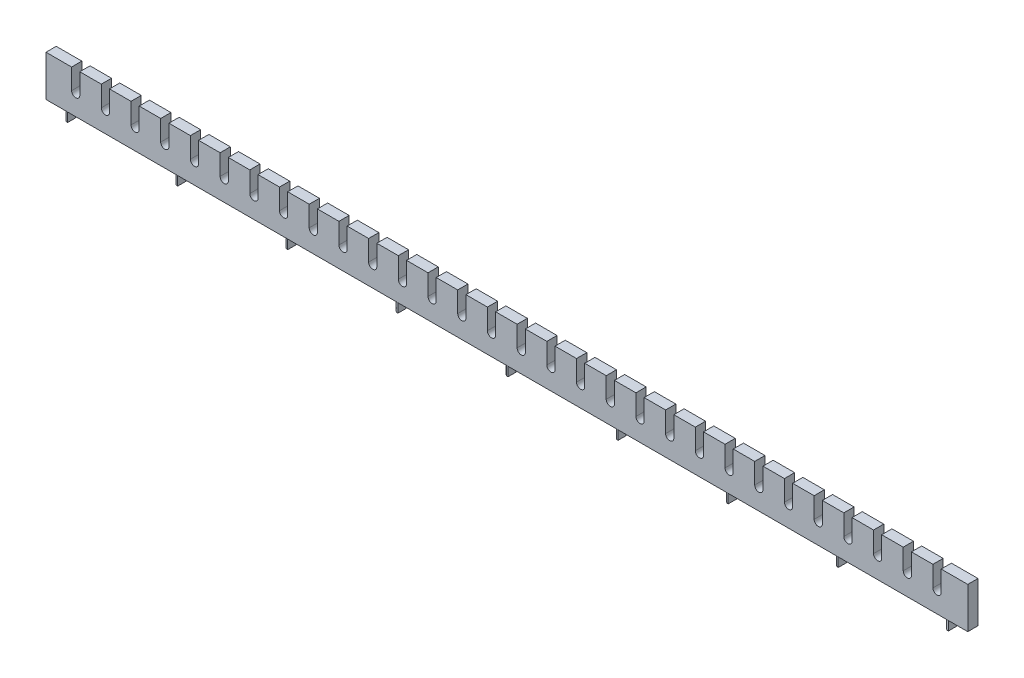
SolidWorks part; units mm, degrees
material "PPE"
ref_plane "Front Plane" through (0, 0, 0) normal (0, 0, 1) x (1, 0, 0)
ref_plane "Top Plane" through (0, 0, 0) normal (0, 1, 0) x (1, 0, 0)
ref_plane "Right Plane" through (0, 0, 0) normal (1, 0, 0) x (0, 0, -1)
sketch "Sketch1" plane through (0, 0, 0) normal (0, 1, 0) x (1, 0, 0)
  line L1 (-285.75, -3.175) -> (285.75, -3.175)
  line L2 (-285.75, -3.175) -> (-285.75, 3.175)
  line L3 (-285.75, 3.175) -> (285.75, 3.175)
  line L4 (285.75, -3.175) -> (285.75, 3.175)
  line L5 (-285.75, -3.175) -> (285.75, 3.175) construction
  line L6 (-285.75, 3.175) -> (285.75, -3.175) construction
  point P0 (0, 0)
  dimension "D1" = 6.35
  dimension "D2" = 571.5
extrude "Boss-Extrude1" add sketch "Sketch1" along normal blind 25.4 contours L2 L3 L4 L1
sketch "Sketch2" plane through (0, 0, 0) normal (0, -1, 0) x (1, 0, 0)
  line L0 (-273.05, 2.54) -> (-273.05, -2.54)
  line L1 (-204.7875, 2.54) -> (-204.7875, -2.54)
  line L2 (-136.525, 2.54) -> (-136.525, -2.54)
  line L3 (-68.2625, 2.54) -> (-68.2625, -2.54)
  line L4 (0, 2.54) -> (0, -2.54)
  line L5 (68.2625, 2.54) -> (68.2625, -2.54)
  line L6 (136.525, 2.54) -> (136.525, -2.54)
  line L7 (204.7875, 2.54) -> (204.7875, -2.54)
  line L8 (273.05, 2.54) -> (273.05, -2.54)
  line L9 (-285.75, 3.175) -> (-285.75, -3.175) construction
  arc A4 (-273.05, 2.54) -> (-273.05, -2.54) centre (-273.05, 0) ccw
  arc A17 (-204.7875, 2.54) -> (-204.7875, -2.54) centre (-204.7875, 0) ccw
  arc A18 (-136.525, 2.54) -> (-136.525, -2.54) centre (-136.525, 0) ccw
  arc A19 (-68.2625, 2.54) -> (-68.2625, -2.54) centre (-68.2625, 0) ccw
  arc A20 (0, 2.54) -> (0, -2.54) centre (0, 0) ccw
  arc A21 (68.2625, 2.54) -> (68.2625, -2.54) centre (68.2625, 0) ccw
  arc A22 (136.525, 2.54) -> (136.525, -2.54) centre (136.525, 0) ccw
  arc A23 (204.7875, 2.54) -> (204.7875, -2.54) centre (204.7875, 0) ccw
  arc A24 (273.05, 2.54) -> (273.05, -2.54) centre (273.05, 0) ccw
  dimension "D1" = 9
  dimension "D4" = 5.08
  dimension "D2" = 12.7
extrude "Boss-Extrude2" add sketch "Sketch2" along normal blind 6.35
sketch "Sketch3" plane through (0, 0, 3.175) normal (0, 0, 1) x (1, 0, 0)
  line L0 (-267.335, 38.1) -> (-267.335, 12.7) construction
  line L1 (-285.75, 25.4) -> (285.75, 25.4) construction
  line L2 (-264.795, 38.1) -> (-264.795, 12.7)
  line L3 (-269.875, 38.1) -> (-269.875, 12.7)
  line L4 (-248.92, 38.1) -> (-248.92, 12.7) construction
  line L7 (-246.38, 38.1) -> (-246.38, 12.7)
  line L10 (-251.46, 38.1) -> (-251.46, 12.7)
  line L19 (-230.505, 38.1) -> (-230.505, 12.7) construction
  line L32 (-227.965, 38.1) -> (-227.965, 12.7)
  line L35 (-233.045, 38.1) -> (-233.045, 12.7)
  line L38 (-212.09, 38.1) -> (-212.09, 12.7) construction
  line L41 (-209.55, 38.1) -> (-209.55, 12.7)
  line L44 (-214.63, 38.1) -> (-214.63, 12.7)
  line L47 (-193.675, 38.1) -> (-193.675, 12.7) construction
  line L50 (-191.135, 38.1) -> (-191.135, 12.7)
  line L53 (-196.215, 38.1) -> (-196.215, 12.7)
  line L56 (-175.26, 38.1) -> (-175.26, 12.7) construction
  line L59 (-172.72, 38.1) -> (-172.72, 12.7)
  line L62 (-177.8, 38.1) -> (-177.8, 12.7)
  line L65 (-156.845, 38.1) -> (-156.845, 12.7) construction
  line L68 (-154.305, 38.1) -> (-154.305, 12.7)
  line L71 (-159.385, 38.1) -> (-159.385, 12.7)
  line L74 (-138.43, 38.1) -> (-138.43, 12.7) construction
  line L77 (-135.89, 38.1) -> (-135.89, 12.7)
  line L80 (-140.97, 38.1) -> (-140.97, 12.7)
  line L83 (-120.015, 38.1) -> (-120.015, 12.7) construction
  line L86 (-117.475, 38.1) -> (-117.475, 12.7)
  line L89 (-122.555, 38.1) -> (-122.555, 12.7)
  line L92 (-101.6, 38.1) -> (-101.6, 12.7) construction
  line L95 (-99.06, 38.1) -> (-99.06, 12.7)
  line L98 (-104.14, 38.1) -> (-104.14, 12.7)
  line L101 (-83.185, 38.1) -> (-83.185, 12.7) construction
  line L104 (-80.645, 38.1) -> (-80.645, 12.7)
  line L105 (-85.725, 38.1) -> (-85.725, 12.7)
  line L106 (-64.77, 38.1) -> (-64.77, 12.7) construction
  line L107 (-62.23, 38.1) -> (-62.23, 12.7)
  line L108 (-67.31, 38.1) -> (-67.31, 12.7)
  line L109 (-46.355, 38.1) -> (-46.355, 12.7) construction
  line L110 (-43.815, 38.1) -> (-43.815, 12.7)
  line L111 (-48.895, 38.1) -> (-48.895, 12.7)
  line L112 (-27.94, 38.1) -> (-27.94, 12.7) construction
  line L113 (-25.4, 38.1) -> (-25.4, 12.7)
  line L114 (-30.48, 38.1) -> (-30.48, 12.7)
  line L115 (-9.525, 38.1) -> (-9.525, 12.7) construction
  line L116 (-285.75, 25.4) -> (-285.75, 0) construction
  line L134 (-6.985, 38.1) -> (-6.985, 12.7)
  line L135 (-12.065, 38.1) -> (-12.065, 12.7)
  line L136 (8.89, 38.1) -> (8.89, 12.7) construction
  line L137 (11.43, 38.1) -> (11.43, 12.7)
  line L138 (6.35, 38.1) -> (6.35, 12.7)
  line L139 (27.305, 38.1) -> (27.305, 12.7) construction
  line L140 (29.845, 38.1) -> (29.845, 12.7)
  line L141 (24.765, 38.1) -> (24.765, 12.7)
  line L142 (45.72, 38.1) -> (45.72, 12.7) construction
  line L143 (48.26, 38.1) -> (48.26, 12.7)
  line L144 (43.18, 38.1) -> (43.18, 12.7)
  line L145 (64.135, 38.1) -> (64.135, 12.7) construction
  line L146 (66.675, 38.1) -> (66.675, 12.7)
  line L147 (61.595, 38.1) -> (61.595, 12.7)
  line L148 (82.55, 38.1) -> (82.55, 12.7) construction
  line L149 (85.09, 38.1) -> (85.09, 12.7)
  line L150 (80.01, 38.1) -> (80.01, 12.7)
  line L151 (100.965, 38.1) -> (100.965, 12.7) construction
  line L152 (103.505, 38.1) -> (103.505, 12.7)
  line L153 (98.425, 38.1) -> (98.425, 12.7)
  line L154 (119.38, 38.1) -> (119.38, 12.7) construction
  line L155 (121.92, 38.1) -> (121.92, 12.7)
  line L156 (116.84, 38.1) -> (116.84, 12.7)
  line L157 (137.795, 38.1) -> (137.795, 12.7) construction
  line L158 (140.335, 38.1) -> (140.335, 12.7)
  line L159 (135.255, 38.1) -> (135.255, 12.7)
  line L160 (156.21, 38.1) -> (156.21, 12.7) construction
  line L161 (158.75, 38.1) -> (158.75, 12.7)
  line L162 (153.67, 38.1) -> (153.67, 12.7)
  line L163 (174.625, 38.1) -> (174.625, 12.7) construction
  line L164 (177.165, 38.1) -> (177.165, 12.7)
  line L165 (172.085, 38.1) -> (172.085, 12.7)
  line L166 (193.04, 38.1) -> (193.04, 12.7) construction
  line L167 (195.58, 38.1) -> (195.58, 12.7)
  line L168 (190.5, 38.1) -> (190.5, 12.7)
  line L169 (211.455, 38.1) -> (211.455, 12.7) construction
  line L170 (213.995, 38.1) -> (213.995, 12.7)
  line L171 (208.915, 38.1) -> (208.915, 12.7)
  line L172 (229.87, 38.1) -> (229.87, 12.7) construction
  line L173 (232.41, 38.1) -> (232.41, 12.7)
  line L174 (227.33, 38.1) -> (227.33, 12.7)
  line L175 (248.285, 38.1) -> (248.285, 12.7) construction
  line L176 (250.825, 38.1) -> (250.825, 12.7)
  line L177 (245.745, 38.1) -> (245.745, 12.7)
  line L178 (266.7, 38.1) -> (266.7, 12.7) construction
  line L179 (269.24, 38.1) -> (269.24, 12.7)
  line L180 (264.16, 38.1) -> (264.16, 12.7)
  arc A0 (-264.795, 38.1) -> (-269.875, 38.1) centre (-267.335, 38.1) ccw
  arc A1 (-269.875, 12.7) -> (-264.795, 12.7) centre (-267.335, 12.7) ccw
  arc A60 (-246.38, 38.1) -> (-251.46, 38.1) centre (-248.92, 38.1) ccw
  arc A61 (-251.46, 12.7) -> (-246.38, 12.7) centre (-248.92, 12.7) ccw
  arc A62 (-227.965, 38.1) -> (-233.045, 38.1) centre (-230.505, 38.1) ccw
  arc A63 (-233.045, 12.7) -> (-227.965, 12.7) centre (-230.505, 12.7) ccw
  arc A64 (-209.55, 38.1) -> (-214.63, 38.1) centre (-212.09, 38.1) ccw
  arc A65 (-214.63, 12.7) -> (-209.55, 12.7) centre (-212.09, 12.7) ccw
  arc A66 (-191.135, 38.1) -> (-196.215, 38.1) centre (-193.675, 38.1) ccw
  arc A67 (-196.215, 12.7) -> (-191.135, 12.7) centre (-193.675, 12.7) ccw
  arc A68 (-172.72, 38.1) -> (-177.8, 38.1) centre (-175.26, 38.1) ccw
  arc A69 (-177.8, 12.7) -> (-172.72, 12.7) centre (-175.26, 12.7) ccw
  arc A70 (-154.305, 38.1) -> (-159.385, 38.1) centre (-156.845, 38.1) ccw
  arc A71 (-159.385, 12.7) -> (-154.305, 12.7) centre (-156.845, 12.7) ccw
  arc A72 (-135.89, 38.1) -> (-140.97, 38.1) centre (-138.43, 38.1) ccw
  arc A73 (-140.97, 12.7) -> (-135.89, 12.7) centre (-138.43, 12.7) ccw
  arc A74 (-117.475, 38.1) -> (-122.555, 38.1) centre (-120.015, 38.1) ccw
  arc A75 (-122.555, 12.7) -> (-117.475, 12.7) centre (-120.015, 12.7) ccw
  arc A76 (-99.06, 38.1) -> (-104.14, 38.1) centre (-101.6, 38.1) ccw
  arc A77 (-104.14, 12.7) -> (-99.06, 12.7) centre (-101.6, 12.7) ccw
  arc A78 (-80.645, 38.1) -> (-85.725, 38.1) centre (-83.185, 38.1) ccw
  arc A79 (-85.725, 12.7) -> (-80.645, 12.7) centre (-83.185, 12.7) ccw
  arc A80 (-62.23, 38.1) -> (-67.31, 38.1) centre (-64.77, 38.1) ccw
  arc A81 (-67.31, 12.7) -> (-62.23, 12.7) centre (-64.77, 12.7) ccw
  arc A82 (-43.815, 38.1) -> (-48.895, 38.1) centre (-46.355, 38.1) ccw
  arc A83 (-48.895, 12.7) -> (-43.815, 12.7) centre (-46.355, 12.7) ccw
  arc A84 (-25.4, 38.1) -> (-30.48, 38.1) centre (-27.94, 38.1) ccw
  arc A85 (-30.48, 12.7) -> (-25.4, 12.7) centre (-27.94, 12.7) ccw
  arc A86 (-6.985, 38.1) -> (-12.065, 38.1) centre (-9.525, 38.1) ccw
  arc A87 (-12.065, 12.7) -> (-6.985, 12.7) centre (-9.525, 12.7) ccw
  arc A88 (11.43, 38.1) -> (6.35, 38.1) centre (8.89, 38.1) ccw
  arc A89 (6.35, 12.7) -> (11.43, 12.7) centre (8.89, 12.7) ccw
  arc A90 (29.845, 38.1) -> (24.765, 38.1) centre (27.305, 38.1) ccw
  arc A91 (24.765, 12.7) -> (29.845, 12.7) centre (27.305, 12.7) ccw
  arc A92 (48.26, 38.1) -> (43.18, 38.1) centre (45.72, 38.1) ccw
  arc A93 (43.18, 12.7) -> (48.26, 12.7) centre (45.72, 12.7) ccw
  arc A94 (66.675, 38.1) -> (61.595, 38.1) centre (64.135, 38.1) ccw
  arc A95 (61.595, 12.7) -> (66.675, 12.7) centre (64.135, 12.7) ccw
  arc A96 (85.09, 38.1) -> (80.01, 38.1) centre (82.55, 38.1) ccw
  arc A97 (80.01, 12.7) -> (85.09, 12.7) centre (82.55, 12.7) ccw
  arc A98 (103.505, 38.1) -> (98.425, 38.1) centre (100.965, 38.1) ccw
  arc A99 (98.425, 12.7) -> (103.505, 12.7) centre (100.965, 12.7) ccw
  arc A100 (121.92, 38.1) -> (116.84, 38.1) centre (119.38, 38.1) ccw
  arc A101 (116.84, 12.7) -> (121.92, 12.7) centre (119.38, 12.7) ccw
  arc A102 (140.335, 38.1) -> (135.255, 38.1) centre (137.795, 38.1) ccw
  arc A103 (135.255, 12.7) -> (140.335, 12.7) centre (137.795, 12.7) ccw
  arc A104 (158.75, 38.1) -> (153.67, 38.1) centre (156.21, 38.1) ccw
  arc A105 (153.67, 12.7) -> (158.75, 12.7) centre (156.21, 12.7) ccw
  arc A106 (177.165, 38.1) -> (172.085, 38.1) centre (174.625, 38.1) ccw
  arc A107 (172.085, 12.7) -> (177.165, 12.7) centre (174.625, 12.7) ccw
  arc A108 (195.58, 38.1) -> (190.5, 38.1) centre (193.04, 38.1) ccw
  arc A109 (190.5, 12.7) -> (195.58, 12.7) centre (193.04, 12.7) ccw
  arc A110 (213.995, 38.1) -> (208.915, 38.1) centre (211.455, 38.1) ccw
  arc A111 (208.915, 12.7) -> (213.995, 12.7) centre (211.455, 12.7) ccw
  arc A112 (232.41, 38.1) -> (227.33, 38.1) centre (229.87, 38.1) ccw
  arc A113 (227.33, 12.7) -> (232.41, 12.7) centre (229.87, 12.7) ccw
  arc A114 (250.825, 38.1) -> (245.745, 38.1) centre (248.285, 38.1) ccw
  arc A115 (245.745, 12.7) -> (250.825, 12.7) centre (248.285, 12.7) ccw
  arc A116 (269.24, 38.1) -> (264.16, 38.1) centre (266.7, 38.1) ccw
  arc A117 (264.16, 12.7) -> (269.24, 12.7) centre (266.7, 12.7) ccw
  point P4 (-267.335, 25.4)
  point P15 (-248.92, 25.4)
  point P22 (-230.505, 25.4)
  point P29 (-212.09, 25.4)
  point P36 (-193.675, 25.4)
  point P43 (-175.26, 25.4)
  point P50 (-156.845, 25.4)
  point P57 (-138.43, 25.4)
  point P64 (-120.015, 25.4)
  point P71 (-101.6, 25.4)
  point P78 (-83.185, 25.4)
  point P85 (-64.77, 25.4)
  point P92 (-46.355, 25.4)
  point P99 (-27.94, 25.4)
  point P106 (-9.525, 25.4)
  point P113 (8.89, 25.4)
  point P120 (27.305, 25.4)
  point P126 (88.9, 25.4)
  point P128 (45.72, 25.4)
  point P135 (64.135, 25.4)
  point P140 (125.73, 25.4)
  point P143 (82.55, 25.4)
  point P150 (100.965, 25.4)
  point P154 (162.56, 25.4)
  point P158 (119.38, 25.4)
  point P165 (137.795, 25.4)
  point P168 (199.39, 25.4)
  point P173 (156.21, 25.4)
  point P180 (174.625, 25.4)
  point P182 (236.22, 25.4)
  point P188 (193.04, 25.4)
  point P195 (211.455, 25.4)
  point P202 (229.87, 25.4)
  point P209 (248.285, 25.4)
  point P210 (52.07, 25.4)
  point P217 (88.9, 25.4)
  point P224 (125.73, 25.4)
  point P231 (162.56, 25.4)
  point P238 (199.39, 25.4)
  point P245 (236.22, 25.4)
  point P252 (52.07, 25.4)
  point P259 (266.7, 25.4)
  dimension "D1" = 5.08
  dimension "D2" = 12.7
  dimension "D3" = 18.415
  dimension "D5" = 18.415
  dimension "D4" = 30
extrude "Cut-Extrude1" cut sketch "Sketch3" against normal through all
